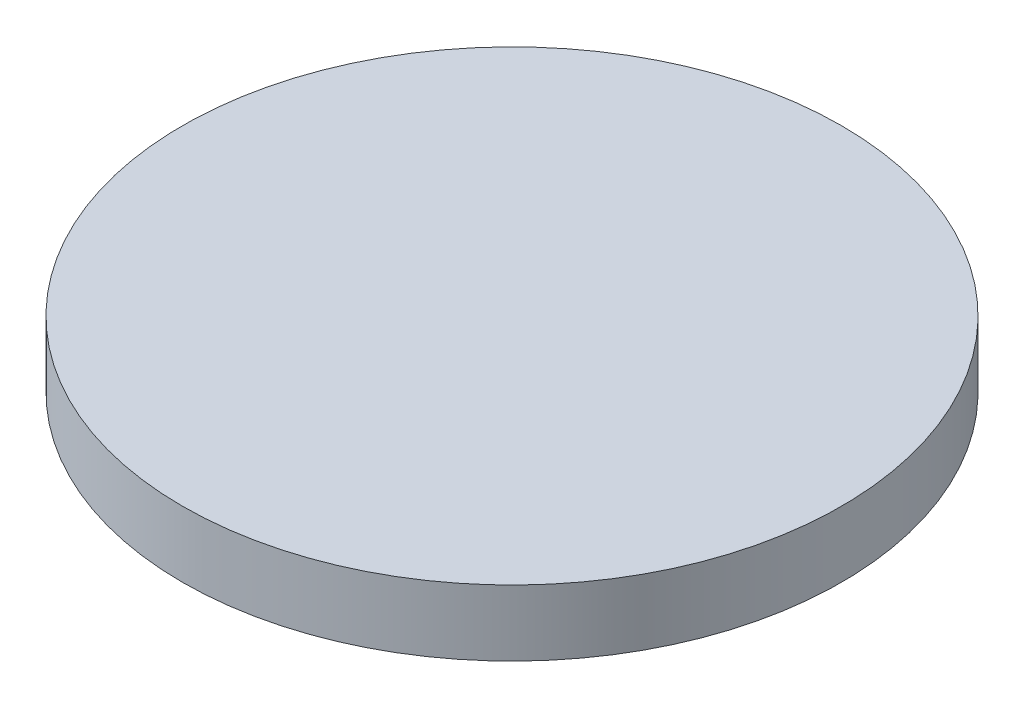
SolidWorks part; units mm, degrees
ref_plane "Front Plane" through (0, 0, 0) normal (0, 0, 1) x (1, 0, 0)
ref_plane "Top Plane" through (0, 0, 0) normal (0, 1, 0) x (1, 0, 0)
ref_plane "Right Plane" through (0, 0, 0) normal (1, 0, 0) x (0, 0, -1)
sketch "Sketch1" plane through (0, 0, 0) normal (0, 1, 0) x (1, 0, 0)
  circle A0 centre (0, 0) radius 63.5
  dimension "D1" = 127
extrude "Boss-Extrude1" add sketch "Sketch1" along normal blind 12.7
